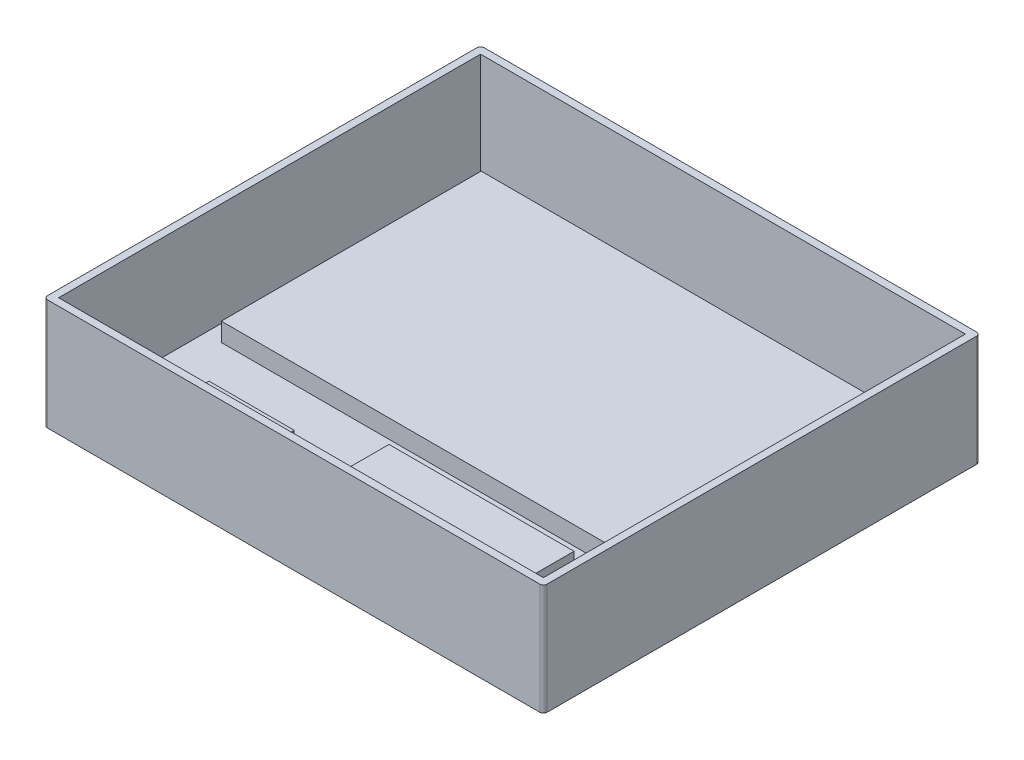
SolidWorks part; units mm, degrees
ref_plane "Front Plane" through (0, 0, 0) normal (0, 0, 1) x (1, 0, 0)
ref_plane "Top Plane" through (0, 0, 0) normal (0, 1, 0) x (1, 0, 0)
ref_plane "Right Plane" through (0, 0, 0) normal (1, 0, 0) x (0, 0, -1)
sketch "Sketch3" plane through (0, 0, 0) normal (0, 1, 0) x (1, 0, 0)
  line L0 (0, -59) -> (0, 59) construction
  line L1 (-67.5, 59) -> (67.5, 59)
  line L2 (-67.5, 59) -> (-67.5, -59)
  line L3 (-67.5, -59) -> (67.5, -59)
  line L4 (67.5, 59) -> (67.5, -59)
  line L5 (-67.5, 0) -> (67.5, 0) construction
  point P8 (0, 0)
  dimension "D1" = 118
  dimension "D2" = 135
extrude "Boss-Extrude1" add sketch "Sketch3" along normal blind 30
sketch "Sketch4" plane through (0, 30, 0) normal (0, 1, 0) x (1, 0, 0)
  line L0 (0, 57) -> (0, -57) construction
  line L1 (-65.5, 57) -> (65.5, 57)
  line L2 (-65.5, 57) -> (-65.5, -57)
  line L3 (-65.5, -57) -> (65.5, -57)
  line L4 (65.5, 57) -> (65.5, -57)
  point P6 (0, 0)
  dimension "D1" = 114
  dimension "D2" = 131
extrude "Cut-Extrude1" cut sketch "Sketch4" against normal offset from surface (28 mm away) 28 up to face at (0, 30, 0)
sketch "Sketch6" plane through (0, 2, 0) normal (0, 1, 0) x (1, 0, 0)
  line L0 (-64.0431, 55.7038) -> (62.9569, 55.7038) construction
  line L1 (-61.0431, 52.7038) -> (59.9569, 52.7038)
  line L2 (-61.0431, 52.7038) -> (-61.0431, -17.4962)
  line L3 (-61.0431, -17.4962) -> (59.9569, -17.4962)
  line L4 (59.9569, 52.7038) -> (59.9569, -17.4962)
  line L5 (-48.6631, -33.1896) -> (-25.6631, -33.1896)
  line L6 (-48.6631, -33.1896) -> (-48.6631, -44.1896)
  line L7 (-48.6631, -44.1896) -> (-25.6631, -44.1896)
  line L8 (-25.6631, -33.1896) -> (-25.6631, -44.1896)
  line L9 (-9.544, -23.6896) -> (40.456, -23.6896)
  line L10 (-9.544, -23.6896) -> (-9.544, -53.6896)
  line L11 (-9.544, -53.6896) -> (40.456, -53.6896)
  line L12 (40.456, -23.6896) -> (40.456, -53.6896)
  line L13 (-11.544, -21.6896) -> (42.456, -21.6896) construction
  line L14 (62.9569, 55.7038) -> (62.9569, -20.4962) construction
  line L15 (62.9569, -20.4962) -> (-64.0431, -20.4962) construction
  line L16 (-64.0431, -20.4962) -> (-64.0431, 55.7038) construction
  line L17 (-64.0431, 17.6038) -> (62.9569, 17.6038) construction
  line L18 (-61.0431, 17.6038) -> (59.9569, 17.6038) construction
  line L19 (42.456, -21.6896) -> (42.456, -55.6896) construction
  line L20 (42.456, -55.6896) -> (-11.544, -55.6896) construction
  line L21 (-11.544, -55.6896) -> (-11.544, -21.6896) construction
  line L22 (-11.544, -38.6896) -> (42.456, -38.6896) construction
  line L23 (-9.544, -38.6896) -> (40.456, -38.6896) construction
  line L24 (-48.6631, -38.6896) -> (-25.6631, -38.6896) construction
  point P16 (-0.5431, 17.6038)
  point P21 (-0.5431, 17.6038)
  point P30 (15.456, -38.6896)
  point P31 (15.456, -38.6896)
  dimension "D1" = 70.2
  dimension "D2" = 121
  dimension "D3" = 30
  dimension "D4" = 50
  dimension "D5" = 11
  dimension "D6" = 23
  dimension "D7" = 76.2
  dimension "D8" = 127
  dimension "D9" = 34
  dimension "D10" = 54
extrude "Boss-Extrude2" add sketch "Sketch6" along normal blind 5
fillet "Fillet1" radius 1 1 edges at (-67.5, 15, 59)
fillet "Fillet2" radius 1 1 edges at (67.5, 15, 59)
fillet "Fillet3" radius 1 1 edges at (67.5, 15, -59)
fillet "Fillet4" radius 1 1 edges at (-67.5, 15, -59)
